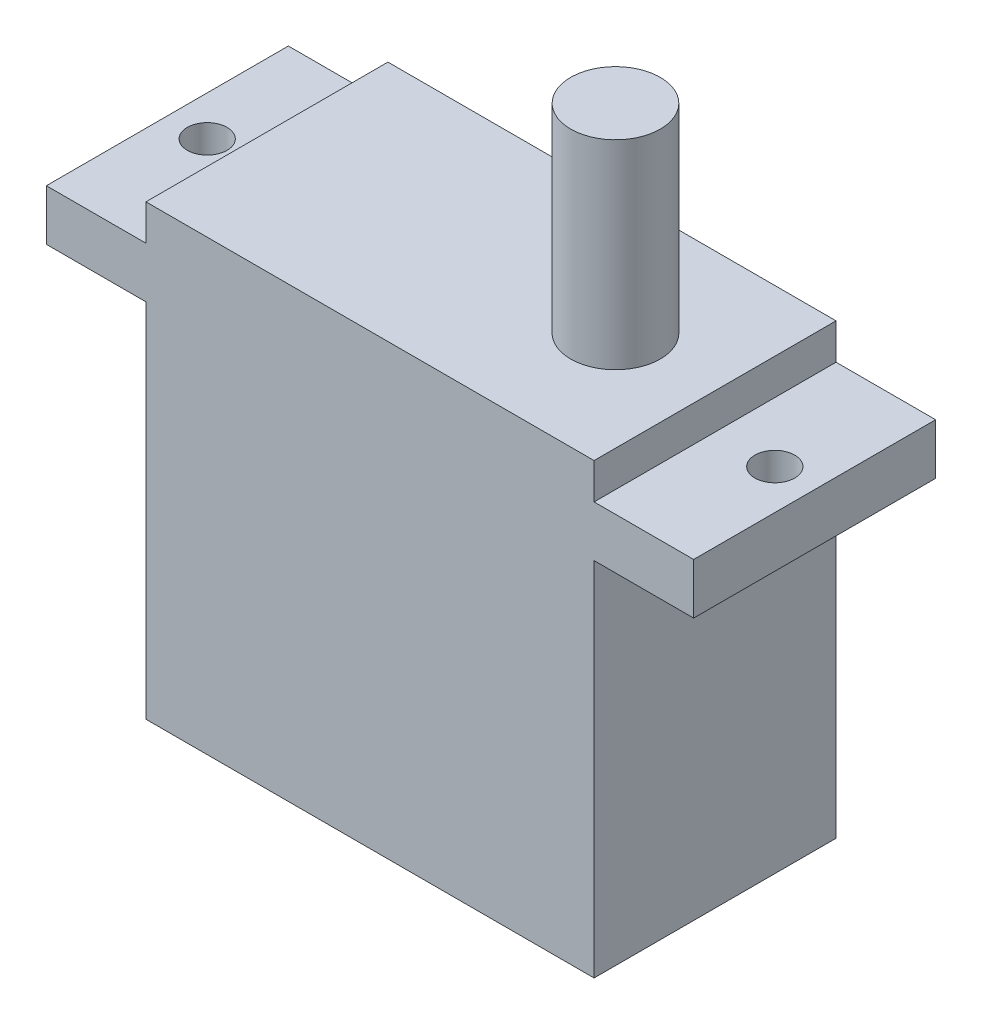
SolidWorks part; units mm, degrees
ref_plane "Front Plane" through (0, 0, 0) normal (0, 0, 1) x (1, 0, 0)
ref_plane "Top Plane" through (0, 0, 0) normal (0, 1, 0) x (1, 0, 0)
ref_plane "Right Plane" through (0, 0, 0) normal (1, 0, 0) x (0, 0, -1)
sketch "Sketch1" plane through (0, 0, 0) normal (0, 1, 0) x (1, 0, 0)
  line L1 (11.25, -6.075) -> (-11.25, -6.075)
  line L2 (11.25, -6.075) -> (11.25, 6.075)
  line L3 (11.25, 6.075) -> (-11.25, 6.075)
  line L4 (-11.25, -6.075) -> (-11.25, 6.075)
  line L5 (11.25, -6.075) -> (-11.25, 6.075) construction
  line L6 (11.25, 6.075) -> (-11.25, -6.075) construction
  point P0 (0, 0)
  dimension "D1" = 22.5
  dimension "D2" = 12.15
extrude "Boss-Extrude1" add sketch "Sketch1" along normal blind 22.5
sketch "Sketch2" plane through (11.25, 0, 0) normal (1, 0, 0) x (0, 0, -1)
  line L0 (6.075, 22.5) -> (6.075, 0) construction
  line L1 (-6.075, 18.15) -> (6.075, 18.15)
  line L2 (-6.075, 18.15) -> (-6.075, 20.7)
  line L3 (-6.075, 20.7) -> (6.075, 20.7)
  line L4 (6.075, 18.15) -> (6.075, 20.7)
  line L5 (-6.075, 18.15) -> (6.075, 20.7) construction
  line L6 (-6.075, 20.7) -> (6.075, 18.15) construction
  line L7 (-6.075, 22.5) -> (6.075, 22.5) construction
  line L8 (-6.075, 22.5) -> (-6.075, 0) construction
  point P0 (0, 19.425)
  dimension "D1" = 2.55
  dimension "D2" = 1.8
extrude "Boss-Extrude2" add sketch "Sketch2" along normal blind 5 contours L3 L4 L1 L2
sketch "Sketch3" plane through (0, 20.7, 0) normal (0, 1, 0) x (1, 0, 0)
  line L0 (16.25, -6.075) -> (16.25, 6.075) construction
  circle A0 centre (14.25, 0) radius 1
  point P2 (14.25, 0)
  dimension "D1" = 2
  dimension "D2" = 2
extrude "Cut-Extrude1" cut sketch "Sketch3" against normal up to surface (2.55 mm away) up to face at (13.75, 18.15, 0)
mirror "Mirror1" about plane through (0, 0, 0) normal (1, 0, 0) of "Cut-Extrude1", "Boss-Extrude2"
sketch "Sketch4" plane through (0, 22.5, 0) normal (0, 1, 0) x (1, 0, 0)
  line L0 (-1000, 0) -> (49000, 0) construction
  line L1 (11.25, -6.075) -> (11.25, 6.075) construction
  circle A0 centre (6.25, 0) radius 2.25
  point P3 (6.9695, 1.7336)
  point P6 (7.4598, 0)
  dimension "D1" = 4.5
  dimension "D2" = 5
extrude "Boss-Extrude3" add sketch "Sketch4" along normal blind 10
